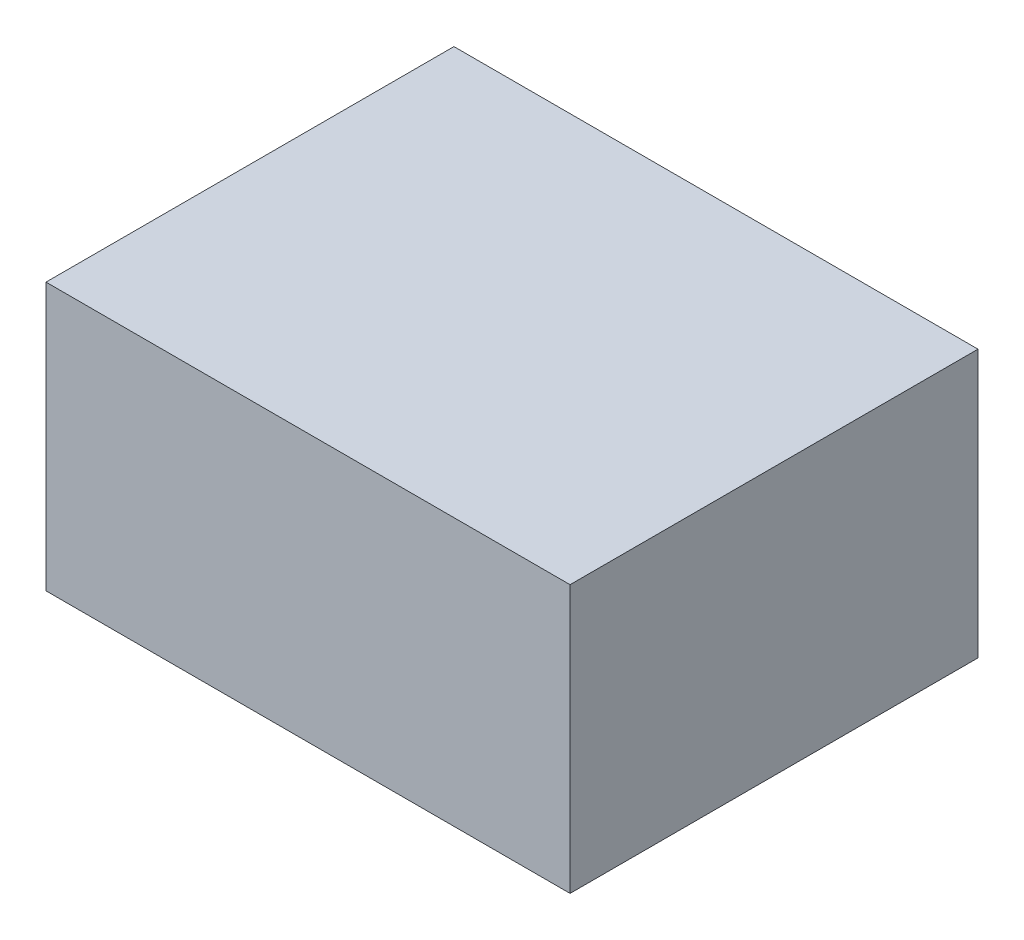
SolidWorks part; units mm, degrees
ref_plane "Front Plane" through (0, 0, 0) normal (0, 0, 1) x (1, 0, 0)
ref_plane "Top Plane" through (0, 0, 0) normal (0, 1, 0) x (1, 0, 0)
ref_plane "Right Plane" through (0, 0, 0) normal (1, 0, 0) x (0, 0, -1)
sketch "Sketch1" plane through (0, 0, 0) normal (0, 1, 0) x (1, 0, 0)
  line L1 (-34.3, 26.7) -> (34.3, 26.7)
  line L2 (-34.3, 26.7) -> (-34.3, -26.7)
  line L3 (-34.3, -26.7) -> (34.3, -26.7)
  line L4 (34.3, 26.7) -> (34.3, -26.7)
  line L5 (-34.3, 26.7) -> (34.3, -26.7) construction
  line L6 (-34.3, -26.7) -> (34.3, 26.7) construction
  point P0 (0, 0)
  dimension "D1" = 68.6
  dimension "D2" = 53.4
extrude "Boss-Extrude1" add sketch "Sketch1" along normal mid plane 35
